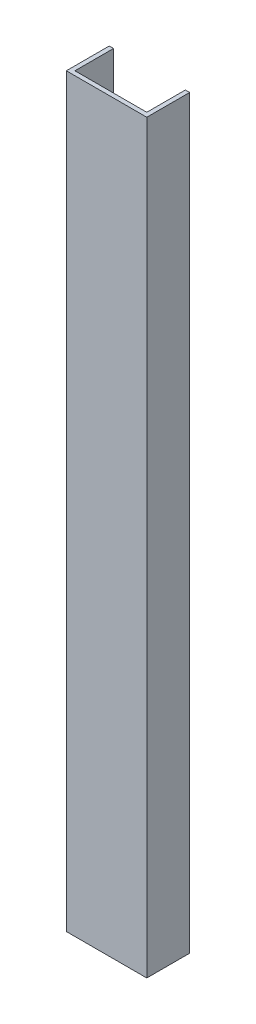
SolidWorks part; units mm, degrees
ref_plane "정면" through (0, 0, 0) normal (0, 0, 1) x (1, 0, 0)
ref_plane "윗면" through (0, 0, 0) normal (0, 1, 0) x (1, 0, 0)
ref_plane "우측면" through (0, 0, 0) normal (1, 0, 0) x (0, 0, -1)
sketch "스케치1" plane through (0, 0, 0) normal (0, 0, 1) x (1, 0, 0)
  line L1 (0, 0) -> (75, 0)
  line L2 (0, 0) -> (0, 695)
  line L3 (0, 695) -> (75, 695)
  line L4 (75, 0) -> (75, 695)
  dimension "D1" = 695
  dimension "D2" = 75
extrude "보스-돌출1" add sketch "스케치1" along normal blind 4
sketch "스케치2" plane through (0, 0, 0) normal (0, 0, -1) x (-1, 0, 0)
  line L0 (0, 0) -> (-75, 0) construction
  line L1 (-75, 695) -> (-71, 695)
  line L2 (-75, 695) -> (-75, 0)
  line L3 (-75, 0) -> (-71, 0)
  line L4 (-71, 695) -> (-71, 0)
  line L6 (0, 695) -> (-4, 695)
  line L7 (0, 695) -> (0, 0)
  line L8 (0, 0) -> (-4, 0)
  line L9 (-4, 695) -> (-4, 0)
  dimension "D1" = 4
  dimension "D2" = 4
extrude "보스-돌출2" add sketch "스케치2" along normal blind 36
